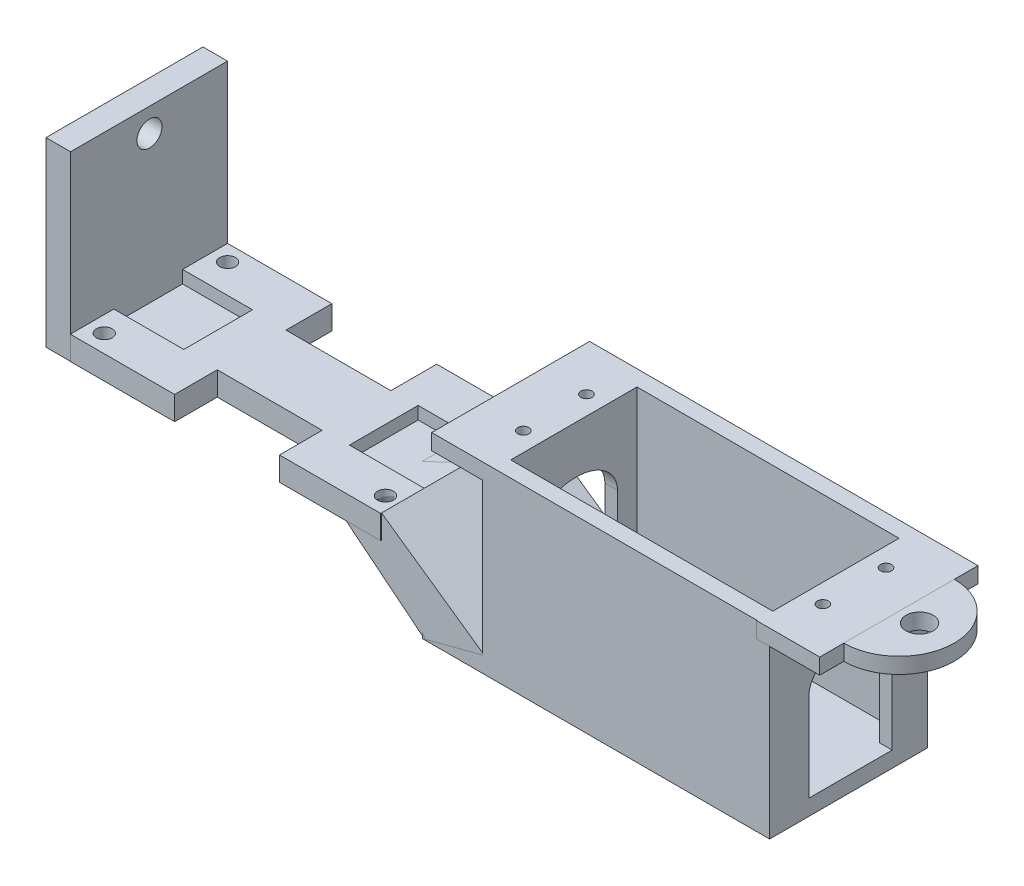
SolidWorks part; units mm, degrees
ref_plane "Front Plane" through (0, 0, 0) normal (0, 0, 1) x (1, 0, 0)
ref_plane "Top Plane" through (0, 0, 0) normal (0, 1, 0) x (1, 0, 0)
ref_plane "Right Plane" through (0, 0, 0) normal (1, 0, 0) x (0, 0, -1)
sketch "Sketch2" plane through (0, 0, 0) normal (0, 1, 0) x (1, 0, 0)
  line L0 (-27.8912, 17.465) -> (18.3368, 17.465)
  line L1 (-25.8592, 14.925) -> (16.3048, 14.925)
  line L2 (-25.8592, 14.925) -> (-25.8592, -5.395)
  line L3 (-25.8592, -5.395) -> (16.3048, -5.395)
  line L4 (16.3048, 14.925) -> (16.3048, -5.395)
  line L5 (18.3368, 17.465) -> (18.3368, -7.935)
  line L6 (-27.8912, -7.935) -> (18.3368, -7.935)
  line L7 (-27.8912, 17.465) -> (-27.8912, -7.935)
  dimension "D1" = 42.164
  dimension "D2" = 20.32
  dimension "D4" = 2.032
  dimension "D3" = 2.032
  dimension "D5" = 2.54
  dimension "D6" = 2.54
extrude "Boss-Extrude1" add sketch "Sketch2" against normal blind 26.924 contours L7 L6 L5 L0
sketch "Sketch6" plane through (-27.8912, 0, 0) normal (-1, 0, 0) x (0, 0, 1)
  line L0 (-11.7822, -26.924) -> (1.6319, -26.924)
  line L1 (1.6319, -26.924) -> (1.6319, -12.8295)
  line L2 (-11.7822, -26.924) -> (-11.7822, -12.8295)
  ellipse E0 centre (-5.0751, -12.8295) end of major axis (-11.7822, -12.8295) minor radius 5.1758 (1.6319, -12.8295) -> (-11.7822, -12.8295) ccw
extrude "Cut-Extrude2" cut sketch "Sketch6" against normal through all
sketch "Sketch7" plane through (0, 0, 0) normal (0, 1, 0) x (1, 0, 0)
  line L0 (-27.8912, -7.935) -> (18.3368, -7.935) construction
  line L1 (16.3048, 17.465) -> (26.4648, 17.465)
  line L2 (16.3048, 17.465) -> (16.3048, -8.0039)
  line L3 (16.3048, -8.0039) -> (26.4648, -8.0039)
  line L4 (26.4648, 17.465) -> (26.4648, -8.0039)
  line L5 (-25.8592, -7.935) -> (-36.0192, -7.935)
  line L6 (-25.8592, -7.935) -> (-25.8592, 17.465)
  line L7 (-25.8592, 17.465) -> (-36.0192, 17.465)
  line L8 (-36.0192, -7.935) -> (-36.0192, 17.465)
  line L9 (18.3368, 17.465) -> (-27.8912, 17.465) construction
  line L12 (-25.8592, 14.925) -> (-25.8592, -5.395) construction
  circle A0 centre (19.3528, 9.7761) radius 0.889
  circle A1 centre (19.3528, -0.3839) radius 0.889
  circle A2 centre (-28.9072, -0.315) radius 0.889
  circle A3 centre (-28.9072, 9.845) radius 0.889
  dimension "D1" = 1.778
  dimension "D7" = 1.778
  dimension "D8" = 1.778
  dimension "D9" = 1.778
  dimension "D2" = 3.048
  dimension "D3" = 10.16
  dimension "D4" = 0
  dimension "D5" = 10.16
  dimension "D6" = 7.62
  dimension "D10" = 3.048
  dimension "D11" = 10.16
  dimension "D12" = 3.048
  dimension "D13" = 3.048
  dimension "D14" = 0
  dimension "D15" = 10.16
  dimension "D16" = 7.62
extrude "Boss-Extrude2" add sketch "Sketch7" against normal blind 2.54
sketch "Sketch8" plane through (0, -26.924, 0) normal (0, -1, 0) x (1, 0, 0)
  line L0 (18.3368, 7.935) -> (18.3368, 1.6319) construction
  line L1 (18.3368, 7.935) -> (-37.5432, 7.935)
  line L2 (18.3368, 7.935) -> (18.3368, -17.465)
  line L3 (18.3368, -17.465) -> (-37.5432, -17.465)
  line L4 (-37.5432, 7.935) -> (-37.5432, -17.465)
  dimension "D1" = 55.88
extrude "Boss-Extrude3" add sketch "Sketch8" along normal blind 2.54
ref_plane "Plane1" through (0, -15.24, 0) normal (0, 1, 0) x (1, 0, 0)
sketch "Sketch9" plane through (0, -15.24, 0) normal (0, 1, 0) x (1, 0, 0)
  line L1 (-44.0991, 17.2299) -> (-94.0355, 17.2299)
  line L2 (-44.0991, 17.2299) -> (-44.0991, -8.0653)
  line L3 (-44.0991, -8.0653) -> (-94.0355, -8.0653)
  line L4 (-94.0355, 17.2299) -> (-94.0355, -8.0653)
  dimension "D1" = 49.9364
  dimension "D2" = 25.2951
extrude "Boss-Extrude4" add sketch "Sketch9" against normal blind 3.81 separate body contours L1 L4 L3 L2
sketch "Sketch11" plane through (0, 0, 7.935) normal (0, 0, 1) x (1, 0, 0)
  line L0 (-44.0991, -15.24) -> (-27.3832, -26.924)
  line L1 (-27.3832, -26.924) -> (-37.0352, -29.464)
  line L2 (-37.0352, -29.464) -> (-51.5303, -17.78)
  line L3 (-51.5303, -17.78) -> (-44.0991, -15.24)
extrude "Boss-Extrude6" add sketch "Sketch11" against normal up to surface (25.1649 mm away) up to face at (-69.0673, -17.145, -17.2299)
sketch "Sketch13" plane through (0, -15.24, 0) normal (0, 1, 0) x (1, 0, 0)
  circle A0 centre (-91.4282, 14.6305) radius 1.27
  circle A1 centre (-46.1844, -5.2133) radius 1.27
  circle A2 centre (-46.1844, 14.6305) radius 1.27
  circle A3 centre (-91.4282, -5.2133) radius 1.27
  dimension "D1" = 2.54
  dimension "D2" = 19.8438
  dimension "D3" = 45.2437
extrude "Cut-Extrude3" cut sketch "Sketch13" against normal through all
sketch "Sketch14" plane through (0, -15.24, 0) normal (0, 1, 0) x (1, 0, 0)
  line L1 (-94.0355, 17.2299) -> (-97.985, 17.2299)
  line L2 (-94.0355, 17.2299) -> (-94.0355, -8.0283)
  line L3 (-94.0355, -8.0283) -> (-97.985, -8.0283)
  line L4 (-97.985, 17.2299) -> (-97.985, -8.0283)
extrude "Boss-Extrude7" add sketch "Sketch14" along normal blind 25.4 and the other way blind 3.81
sketch "Sketch15" plane through (-94.0355, 0, 0) normal (1, 0, 0) x (0, 0, -1)
  line L0 (-8.0283, 10.16) -> (17.2299, 10.16) construction
  line L1 (-8.0283, -15.24) -> (-8.0283, 10.16) construction
  circle A0 centre (4.6717, 6.35) radius 2.0149
  dimension "D1" = 3.81
  dimension "D2" = 12.7
extrude "Cut-Extrude4" cut sketch "Sketch15" against normal blind 25.4 contours A0
sketch "Sketch16" plane through (0, -15.24, 0) normal (0, 1, 0) x (1, 0, 0)
  line L1 (-77.2525, 17.2299) -> (-60.383, 17.2299)
  line L2 (-77.2525, 17.2299) -> (-77.2525, 9.8509)
  line L3 (-77.2525, 9.8509) -> (-60.383, 9.8509)
  line L4 (-60.383, 17.2299) -> (-60.383, 9.8509)
  line L5 (-77.2525, -1.2064) -> (-60.383, -1.2064)
  line L6 (-77.2525, -1.2064) -> (-77.2525, -8.0653)
  line L7 (-77.2525, -8.0653) -> (-60.383, -8.0653)
  line L8 (-60.383, -1.2064) -> (-60.383, -8.0653)
extrude "Cut-Extrude5" cut sketch "Sketch16" against normal blind 25.4
sketch "Sketch17" plane through (0, -15.24, 0) normal (0, 1, 0) x (1, 0, 0)
  line L1 (-44.0991, 9.9927) -> (-56.1302, 9.9927)
  line L2 (-44.0991, 9.9927) -> (-44.0991, -1.0646)
  line L3 (-44.0991, -1.0646) -> (-56.1302, -1.0646)
  line L4 (-56.1302, 9.9927) -> (-56.1302, -1.0646)
  line L5 (-94.0355, 9.9927) -> (-82.7812, 9.9927)
  line L6 (-94.0355, 9.9927) -> (-94.0355, -1.0646)
  line L7 (-94.0355, -1.0646) -> (-82.7812, -1.0646)
  line L8 (-82.7812, 9.9927) -> (-82.7812, -1.0646)
extrude "Cut-Extrude6" cut sketch "Sketch17" against normal blind 2.032
ref_plane "Plane2" through (0, -2.54, 0) normal (0, -1, 0) x (-1, 0, 0)
sketch "Sketch18" plane through (0, -2.54, 0) normal (0, -1, 0) x (-1, 0, 0)
  line L0 (97.9491, 13.4199) -> (97.9491, -4.3601)
  line L1 (97.985, 17.2299) -> (97.985, -8.0283) construction
  line L2 (77.2525, 17.2299) -> (94.0355, 17.2299) construction
  arc A0 (97.9491, 13.4199) -> (97.9491, -4.3601) centre (97.9491, 4.5299) cw
  circle A1 centre (101.287, 4.5299) radius 2.1844
  dimension "D1" = 4.3688
  dimension "D4" = 8.89
  dimension "D2" = 3.302
  dimension "D3" = 12.7
  dimension "D5" = 0
extrude "Boss-Extrude8" add sketch "Sketch18" against normal blind 3.81 contours A0 L0
sketch "Sketch19" plane through (0, -2.54, 0) normal (0, -1, 0) x (-1, 0, 0)
  line L0 (97.985, 12.4569) -> (-42.9701, 12.4569) construction
  line L1 (-26.4648, 13.655) -> (-26.4648, -4.125)
  line L2 (-26.4648, 17.465) -> (36.0192, 17.465) construction
  line L5 (-26.4648, -8.0039) -> (-26.4648, 17.465) construction
  arc A0 (-26.4648, 13.655) -> (-26.4648, -4.125) centre (-26.4648, 4.765) ccw
  circle A1 centre (-29.7668, 4.765) radius 2.1844
  dimension "D1" = 4.3688
  dimension "D5" = 8.89
  dimension "D2" = 12.7
  dimension "D3" = 3.302
  dimension "D4" = 0
  dimension "D6" = 0
extrude "Boss-Extrude9" add sketch "Sketch19" against normal blind 2.54 separate body contours A0 L1
sketch "Sketch20" plane through (0, -15.24, 0) normal (0, 1, 0) x (1, 0, 0)
  line L0 (-97.985, -8.0283) -> (26.5762, -8.0039)
  dimension "D1" = 124.5612
